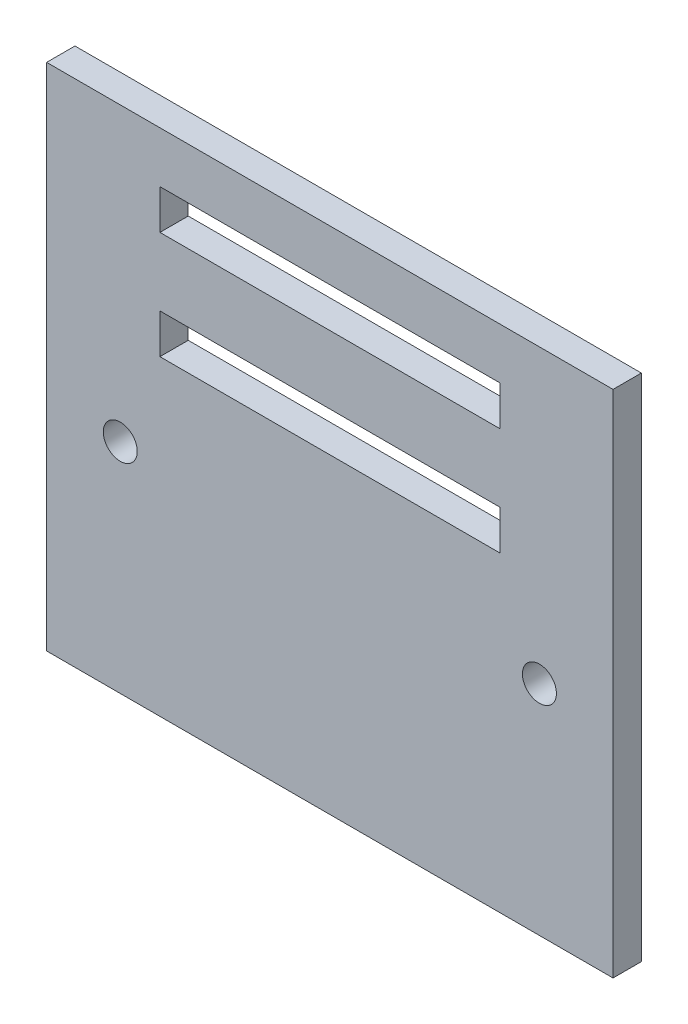
SolidWorks part; units mm, degrees
material "PBT General Purpose"
ref_plane "Front Plane" through (0, 0, 0) normal (0, 0, 1) x (1, 0, 0)
ref_plane "Top Plane" through (0, 0, 0) normal (0, 1, 0) x (1, 0, 0)
ref_plane "Right Plane" through (0, 0, 0) normal (1, 0, 0) x (0, 0, -1)
sketch "frame_outline" plane through (0, 0, 0) normal (0, 0, 1) x (1, 0, 0)
  line L123 (0.65, 1.925) -> (4.35, 1.925) construction
  line L124 (0, 0) -> (5, 0)
  line L125 (0, 0) -> (0, 4.5)
  line L126 (0, 4.5) -> (5, 4.5)
  line L127 (5, 0) -> (5, 4.5)
  line L132 (1, 3.1) -> (4, 3.1)
  line L133 (1, 3.1) -> (1, 2.75)
  line L134 (1, 2.75) -> (4, 2.75)
  line L135 (4, 3.1) -> (4, 2.75)
  line L136 (1, 3.7) -> (4, 3.7)
  line L137 (1, 3.7) -> (1, 4.05)
  line L138 (1, 4.05) -> (4, 4.05)
  line L139 (4, 3.7) -> (4, 4.05)
  circle A0 centre (0.65, 1.925) radius 0.15
  circle A1 centre (4.35, 1.925) radius 0.15
  point P12 (2.5, 2.75)
  point P13 (2.5, 0)
  point P18 (2.5, 1.925)
  point P19 (1, 2.925)
  dimension "D7" = 0.3
  dimension "D8" = 0.3
  dimension "D1" = 3
  dimension "D2" = 5
  dimension "D3" = 0.35
  dimension "D4" = 4.5
  dimension "D5" = 2.75
  dimension "D6" = 3.7
  dimension "D9" = 1.85
  dimension "D10" = 1
extrude "Boss-Extrude1" add sketch "frame_outline" along normal mid plane 0.25
equation "\"t\"= 0.25'thickness of the sheets"
equation "\"t_cf\"= 0.115'thickness of single carbon fiber layer"
equation "\"t_kapton\"= 0.025'thickness of single Kapton flex layer"
equation "\"t_fr4\"= 0.1'thickness of FR4 with copper layer"
equation "\"joint_flex\"= 0.1'Width of flextures gap"
equation "\"joint_flex_eff\"= 0.02'Width of flecture after castelation"
equation "\"joint_fold\"= 0.2'Width of folding joints for 90deg fold"
equation "\"gap_tolerance\"= 0.002'Width to have interfecence fit between carbon fiber inserts"
equation "\"assemble_angle\"= 90'Angle of assembly parts"
equation "\"D1@Boss-Extrude1\"=\"t\""
equation "\"link_lift\"= 0.5'Actuation linkage amplification for the lift motion"
equation "\"link_swing\"= 0.45'Actuation linkage amplification for the swing motion"
equation "\"D3@frame_outline\"=0.35"
